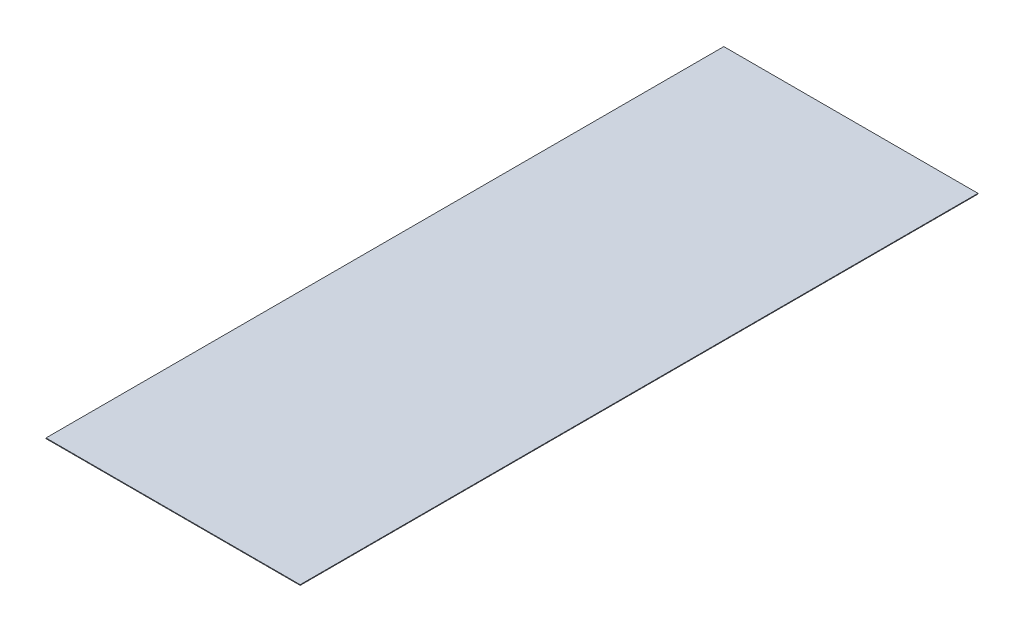
SolidWorks part; units mm, degrees
material "ASTM A36 Acero"
ref_plane "Alzado" through (0, 0, 0) normal (0, 0, 1) x (1, 0, 0)
ref_plane "Planta" through (0, 0, 0) normal (0, 1, 0) x (1, 0, 0)
ref_plane "Vista lateral" through (0, 0, 0) normal (1, 0, 0) x (0, 0, -1)
sketch "Croquis1" plane through (0, 0, 0) normal (0, 1, 0) x (1, 0, 0)
  line L1 (-457.2, -1219.2) -> (457.2, -1219.2)
  line L2 (-457.2, -1219.2) -> (-457.2, 1219.2)
  line L3 (-457.2, 1219.2) -> (457.2, 1219.2)
  line L4 (457.2, -1219.2) -> (457.2, 1219.2)
  line L5 (-457.2, -1219.2) -> (457.2, 1219.2) construction
  line L6 (-457.2, 1219.2) -> (457.2, -1219.2) construction
  point P0 (0, 0)
  dimension "D1" = 2438.4
  dimension "D2" = 914.4
extrude "Saliente-Extruir1" add sketch "Croquis1" along normal blind 2.3
